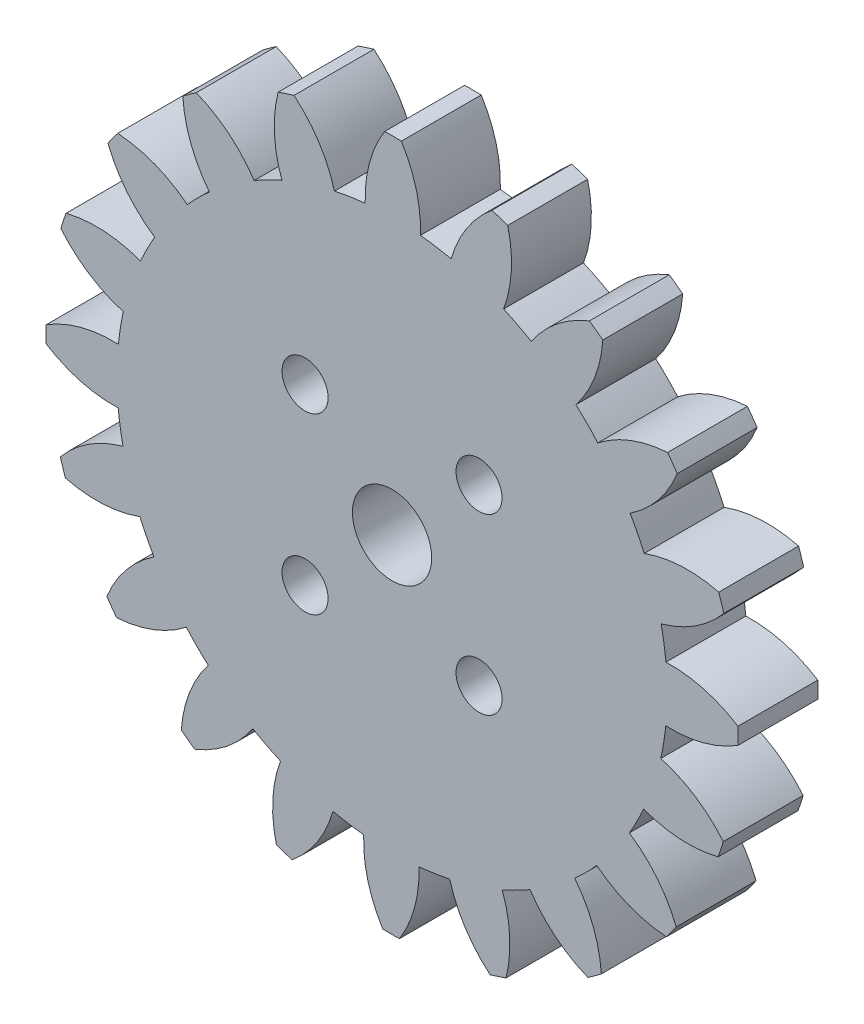
SolidWorks part; units mm, degrees
material "ABS"
ref_plane "Plan de face" through (0, 0, 0) normal (0, 0, 1) x (1, 0, 0)
ref_plane "Plan de dessus" through (0, 0, 0) normal (0, 1, 0) x (1, 0, 0)
ref_plane "Plan de droite" through (0, 0, 0) normal (1, 0, 0) x (0, 0, -1)
sketch "Esquisse1" plane through (0, 0, 0) normal (0, 0, 1) x (1, 0, 0)
  arc A160 (4.5803, -21.3891) -> (7.7939, -26.3724) centre (14.2133, -18.7048) ccw
  arc A161 (7.7939, -26.3724) -> (9.0538, -25.9669) centre (0, 0) ccw
  arc A162 (9.0538, -25.9669) -> (8.757, -20.0446) centre (-0.633, -23.4838) ccw
  arc A163 (8.757, -20.0446) -> (10.9657, -18.9268) centre (0, 0) ccw
  arc A164 (10.9657, -18.9268) -> (15.562, -22.6732) centre (19.2978, -13.3972) ccw
  arc A165 (15.562, -22.6732) -> (16.6349, -21.8982) centre (0, 0) ccw
  arc A166 (16.6349, -21.8982) -> (14.5225, -16.3575) centre (6.6549, -22.53) ccw
  arc A167 (14.5225, -16.3575) -> (16.2777, -14.6119) centre (0, 0) ccw
  arc A168 (16.2777, -14.6119) -> (21.8067, -16.7546) centre (22.4932, -6.7782) ccw
  arc A169 (21.8067, -16.7546) -> (22.5876, -15.686) centre (0, 0) ccw
  arc A170 (22.5876, -15.686) -> (18.8665, -11.0692) centre (13.2913, -19.3709) ccw
  arc A171 (18.8665, -11.0692) -> (19.9964, -8.8667) centre (0, 0) ccw
  arc A172 (19.9964, -8.8667) -> (25.9169, -9.1959) centre (23.4869, 0.5044) ccw
  arc A173 (25.9169, -9.1959) -> (26.3293, -7.9383) centre (0, 0) ccw
  arc A174 (26.3293, -7.9383) -> (21.3637, -4.6974) centre (18.6267, -14.3155) ccw
  arc A175 (21.3637, -4.6974) -> (21.7576, -2.2535) centre (0, 0) ccw
  arc A176 (21.7576, -2.2535) -> (27.4901, -0.7371) centre (22.1815, 7.7375) ccw
  arc A177 (27.4901, -0.7371) -> (27.4937, 0.5865) centre (0, 0) ccw
  arc A178 (27.4937, 0.5865) -> (21.7696, 2.1343) centre (22.1388, -7.8589) ccw
  arc A179 (21.7696, 2.1343) -> (21.3891, 4.5803) centre (0, 0) ccw
  arc A180 (21.3891, 4.5803) -> (26.3724, 7.7939) centre (18.7048, 14.2133) ccw
  arc A181 (26.3724, 7.7939) -> (25.9669, 9.0538) centre (0, 0) ccw
  arc A182 (25.9669, 9.0538) -> (20.0446, 8.757) centre (23.4838, -0.633) ccw
  arc A183 (20.0446, 8.757) -> (18.9268, 10.9657) centre (0, 0) ccw
  arc A184 (18.9268, 10.9657) -> (22.6732, 15.562) centre (13.3972, 19.2978) ccw
  arc A185 (22.6732, 15.562) -> (21.8982, 16.6349) centre (0, 0) ccw
  arc A186 (21.8982, 16.6349) -> (16.3575, 14.5225) centre (22.53, 6.6549) ccw
  arc A187 (16.3575, 14.5225) -> (14.6119, 16.2777) centre (0, 0) ccw
  arc A188 (14.6119, 16.2777) -> (16.7546, 21.8067) centre (6.7782, 22.4932) ccw
  arc A189 (16.7546, 21.8067) -> (15.686, 22.5876) centre (0, 0) ccw
  arc A190 (15.686, 22.5876) -> (11.0692, 18.8665) centre (19.3709, 13.2913) ccw
  arc A191 (11.0692, 18.8665) -> (8.8667, 19.9964) centre (0, 0) ccw
  arc A192 (8.8667, 19.9964) -> (9.1959, 25.9169) centre (-0.5044, 23.4869) ccw
  arc A193 (9.1959, 25.9169) -> (7.9383, 26.3293) centre (0, 0) ccw
  arc A194 (7.9383, 26.3293) -> (4.6974, 21.3637) centre (14.3155, 18.6267) ccw
  arc A195 (4.6974, 21.3637) -> (2.2535, 21.7576) centre (0, 0) ccw
  arc A196 (2.2535, 21.7576) -> (0.7371, 27.4901) centre (-7.7375, 22.1815) ccw
  arc A197 (0.7371, 27.4901) -> (-0.5865, 27.4937) centre (0, 0) ccw
  arc A198 (-0.5865, 27.4937) -> (-2.1343, 21.7696) centre (7.8589, 22.1388) ccw
  arc A199 (-2.1343, 21.7696) -> (-4.5803, 21.3891) centre (0, 0) ccw
  arc A200 (-4.5803, 21.3891) -> (-7.7939, 26.3724) centre (-14.2133, 18.7048) ccw
  arc A201 (-7.7939, 26.3724) -> (-9.0538, 25.9669) centre (0, 0) ccw
  arc A202 (-9.0538, 25.9669) -> (-8.757, 20.0446) centre (0.633, 23.4838) ccw
  arc A203 (-8.757, 20.0446) -> (-10.9657, 18.9268) centre (0, 0) ccw
  arc A204 (-10.9657, 18.9268) -> (-15.562, 22.6732) centre (-19.2978, 13.3972) ccw
  arc A205 (-15.562, 22.6732) -> (-16.6349, 21.8982) centre (0, 0) ccw
  arc A206 (-16.6349, 21.8982) -> (-14.5225, 16.3575) centre (-6.6549, 22.53) ccw
  arc A207 (-14.5225, 16.3575) -> (-16.2777, 14.6119) centre (0, 0) ccw
  arc A208 (-16.2777, 14.6119) -> (-21.8067, 16.7546) centre (-22.4932, 6.7782) ccw
  arc A209 (-21.8067, 16.7546) -> (-22.5876, 15.686) centre (0, 0) ccw
  arc A210 (-22.5876, 15.686) -> (-18.8665, 11.0692) centre (-13.2913, 19.3709) ccw
  arc A211 (-18.8665, 11.0692) -> (-19.9964, 8.8667) centre (0, 0) ccw
  arc A212 (-19.9964, 8.8667) -> (-25.9169, 9.1959) centre (-23.4869, -0.5044) ccw
  arc A213 (-25.9169, 9.1959) -> (-26.3293, 7.9383) centre (0, 0) ccw
  arc A214 (-26.3293, 7.9383) -> (-21.3637, 4.6974) centre (-18.6267, 14.3155) ccw
  arc A215 (-21.3637, 4.6974) -> (-21.7576, 2.2535) centre (0, 0) ccw
  arc A216 (-21.7576, 2.2535) -> (-27.4901, 0.7371) centre (-22.1815, -7.7375) ccw
  arc A217 (-27.4901, 0.7371) -> (-27.4937, -0.5865) centre (0, 0) ccw
  arc A218 (-27.4937, -0.5865) -> (-21.7696, -2.1343) centre (-22.1388, 7.8589) ccw
  arc A219 (-21.7696, -2.1343) -> (-21.3891, -4.5803) centre (0, 0) ccw
  arc A220 (-21.3891, -4.5803) -> (-26.3724, -7.7939) centre (-18.7048, -14.2133) ccw
  arc A221 (-26.3724, -7.7939) -> (-25.9669, -9.0538) centre (0, 0) ccw
  arc A222 (-25.9669, -9.0538) -> (-20.0446, -8.757) centre (-23.4838, 0.633) ccw
  arc A223 (-20.0446, -8.757) -> (-18.9268, -10.9657) centre (0, 0) ccw
  arc A224 (-18.9268, -10.9657) -> (-22.6732, -15.562) centre (-13.3972, -19.2978) ccw
  arc A225 (-22.6732, -15.562) -> (-21.8982, -16.6349) centre (0, 0) ccw
  arc A226 (-21.8982, -16.6349) -> (-16.3575, -14.5225) centre (-22.53, -6.6549) ccw
  arc A227 (-16.3575, -14.5225) -> (-14.6119, -16.2777) centre (0, 0) ccw
  arc A228 (-14.6119, -16.2777) -> (-16.7546, -21.8067) centre (-6.7782, -22.4932) ccw
  arc A229 (-16.7546, -21.8067) -> (-15.686, -22.5876) centre (0, 0) ccw
  arc A230 (-15.686, -22.5876) -> (-11.0692, -18.8665) centre (-19.3709, -13.2913) ccw
  arc A231 (-11.0692, -18.8665) -> (-8.8667, -19.9964) centre (0, 0) ccw
  arc A232 (-8.8667, -19.9964) -> (-9.1959, -25.9169) centre (0.5044, -23.4869) ccw
  arc A233 (-9.1959, -25.9169) -> (-7.9383, -26.3293) centre (0, 0) ccw
  arc A234 (-7.9383, -26.3293) -> (-4.6974, -21.3637) centre (-14.3155, -18.6267) ccw
  arc A235 (-4.6974, -21.3637) -> (-2.2535, -21.7576) centre (0, 0) ccw
  arc A236 (-2.2535, -21.7576) -> (-0.7371, -27.4901) centre (7.7375, -22.1815) ccw
  arc A237 (-0.7371, -27.4901) -> (0.5865, -27.4937) centre (0, 0) ccw
  arc A238 (0.5865, -27.4937) -> (2.1343, -21.7696) centre (-7.8589, -22.1388) ccw
  arc A239 (2.1343, -21.7696) -> (4.5803, -21.3891) centre (0, 0) ccw
extrude "Boss.-Extru.1" add sketch "Esquisse1" along normal blind 6.35
sketch "Esquisse2" plane through (0, 0, 0) normal (0, 0, -1) x (-1, 0, 0)
  circle A0 centre (0, 0) radius 3.15
  arc A1 (2.0142, -2.4219) -> (-2.0142, -2.4219) centre (0, 0) ccw construction
  circle A2 centre (-6.9148, -6.9148) radius 1.83
  circle A4 centre (-6.9148, 6.9148) radius 1.83
  circle A5 centre (6.9148, 6.9148) radius 1.83
  circle A6 centre (6.9148, -6.9148) radius 1.83
  arc A7 (-6.1737, -8.503) -> (-6.9148, -5.1622) centre (-6.9148, -6.9148) ccw construction
  point P11 (-6.9148, 6.9148)
  point P20 (0, 0)
  dimension "D1" = 4
  dimension "D2" = 3.66
extrude "Enlèv. mat.-Extru.1" cut sketch "Esquisse2" against normal up to next
